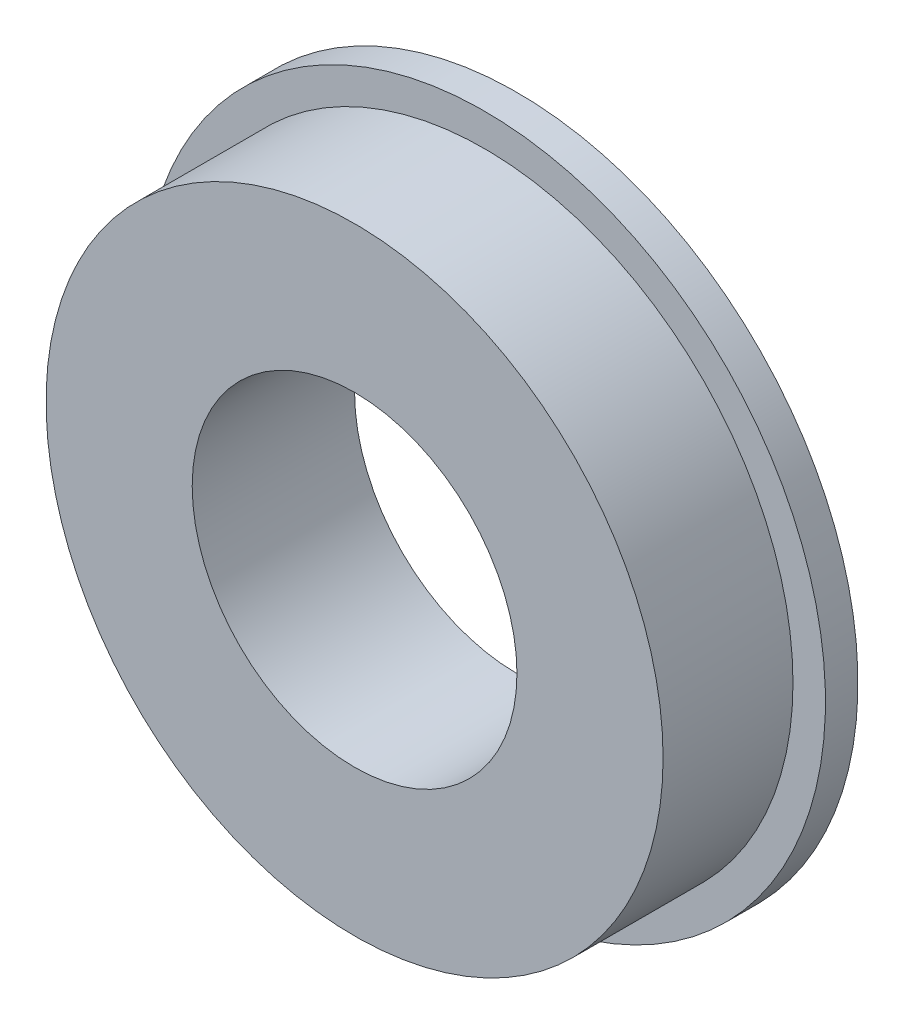
SolidWorks part; units mm, degrees
ref_plane "前视基准面" through (0, 0, 0) normal (0, 0, 1) x (1, 0, 0)
ref_plane "上视基准面" through (0, 0, 0) normal (0, 1, 0) x (1, 0, 0)
ref_plane "右视基准面" through (0, 0, 0) normal (1, 0, 0) x (0, 0, -1)
sketch "草图1" plane through (0, 0, 0) normal (0, 0, 1) x (1, 0, 0)
  circle A0 centre (0, 0) radius 9.5
  circle A1 centre (0, 0) radius 5
  dimension "D1" = 10
  dimension "D2" = 19
extrude "凸台-拉伸1" add sketch "草图1" along normal blind 4
sketch "草图2" plane through (0, 0, 0) normal (0, 0, -1) x (-1, 0, 0)
  circle A0 centre (0, 0) radius 5
  circle A1 centre (0, 0) radius 10.5
  point P4 (0, 0)
  dimension "D1" = 21
extrude "凸台-拉伸2" add sketch "草图2" along normal blind 1
